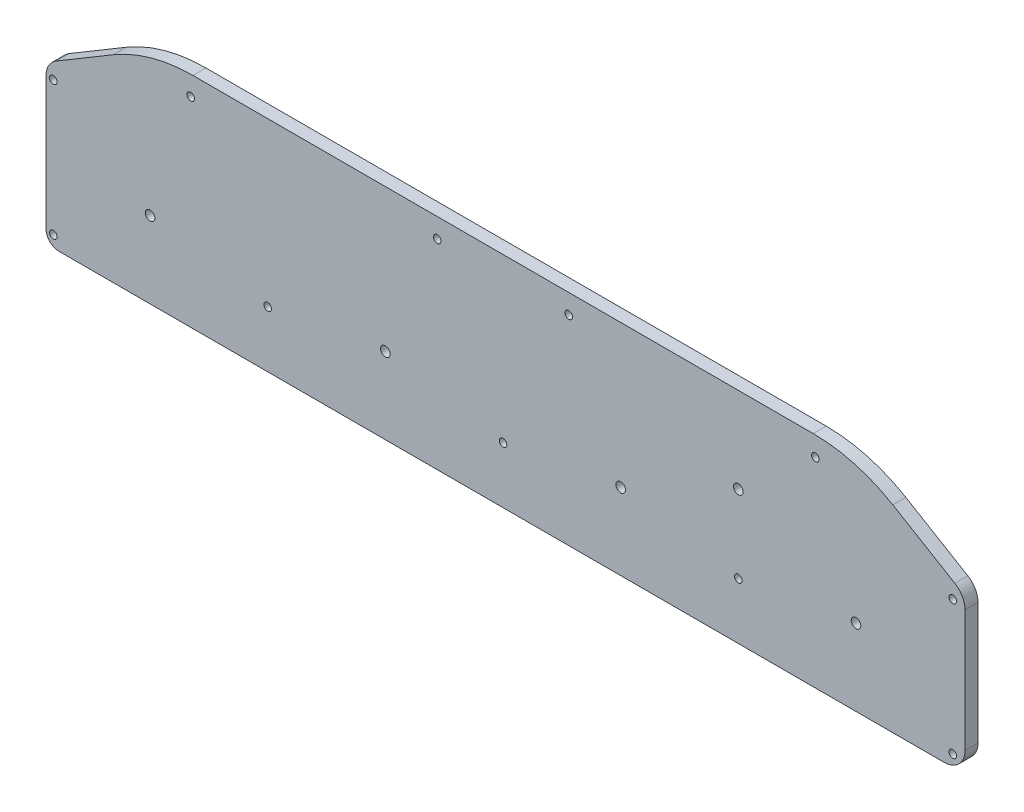
SolidWorks part; units mm, degrees
ref_plane "Front Plane" through (0, 0, 0) normal (0, 0, 1) x (1, 0, 0)
ref_plane "Top Plane" through (0, 0, 0) normal (0, 1, 0) x (1, 0, 0)
ref_plane "Right Plane" through (0, 0, 0) normal (1, 0, 0) x (0, 0, -1)
sketch "Sketch1" plane through (0, 0, 0) normal (0, 0, 1) x (1, 0, 0)
  line L0 (-228.6, 0) -> (228.6, 0) construction
  line L1 (0, -1000) -> (0, 49000) construction
  line L2 (0, 0) -> (0, -6.35)
  line L3 (-149.6188, -37.4478) -> (-217.2874, -37.4478)
  line L4 (226.06, -27.2878) -> (226.06, 32.3239)
  line L5 (220.0588, -31.7528) -> (-220.0588, -31.7528) construction
  line L6 (-223.6374, 33.766) -> (-223.6374, -31.0978)
  line L7 (-149.6188, -37.4478) -> (215.9, -37.4478)
  line L8 (-151.7577, 69.85) -> (151.7577, 69.85)
  line L9 (-240.1744, 69.85) -> (-240.1744, -37.4478) construction
  line L10 (-190.7328, 59.1281) -> (-218.6741, 42.4964)
  line L16 (190.7328, 59.1281) -> (221.0967, 41.0544)
  line L20 (-82.9742, 60.325) -> (-152.8242, 60.325) construction
  line L21 (-32.1742, 60.325) -> (-82.9742, 60.325) construction
  line L22 (32.1742, 60.325) -> (82.9742, 60.325) construction
  line L23 (82.9742, 60.325) -> (152.8242, 60.325) construction
  circle A0 centre (-172.72, 0) radius 50.8 construction
  circle A1 centre (172.72, 0) radius 50.8 construction
  circle A2 centre (-57.5742, 0) radius 50.8 construction
  circle A3 centre (57.5725, 0) radius 50.8 construction
  circle A4 centre (-172.72, 0) radius 2.35
  circle A5 centre (-57.5742, 0) radius 2.35
  circle A6 centre (57.5725, 0) radius 2.35
  circle A7 centre (172.72, 0) radius 2.35
  circle A8 centre (-172.72, 0) radius 32 construction
  circle A9 centre (-57.5742, 0) radius 32 construction
  circle A10 centre (57.5725, 0) radius 32 construction
  circle A11 centre (172.72, 0) radius 32 construction
  circle A12 centre (-115.1471, 27.9528) radius 32 construction
  circle A13 centre (-0.0009, 27.952) radius 32 construction
  circle A14 centre (115.1462, 27.9511) radius 32 construction
  circle A15 centre (-172.72, 0) radius 44 construction
  circle A16 centre (220.0588, -31.7528) radius 1.85
  circle A17 centre (115.1462, 27.9511) radius 2.35
  circle A18 centre (-220.0588, -31.7528) radius 1.85
  arc A19 (-217.2874, -37.4478) -> (-223.6374, -31.0978) centre (-217.2874, -31.0978) cw
  arc A20 (-223.6374, 33.766) -> (-218.6741, 42.4964) centre (-213.4774, 33.766) cw
  arc A21 (215.9, -37.4478) -> (226.06, -27.2878) centre (215.9, -27.2878) ccw
  arc A23 (221.0967, 41.0544) -> (226.06, 32.3239) centre (215.9, 32.3239) cw
  arc A24 (151.7577, 69.85) -> (190.7328, 59.1281) centre (151.7577, -6.35) cw
  arc A25 (-151.7577, 69.85) -> (-190.7328, 59.1281) centre (-151.7577, -6.35) ccw
  circle A37 centre (-32.1742, 60.325) radius 1.85
  circle A38 centre (-152.8242, 60.325) radius 1.85
  circle A39 centre (152.8242, 60.325) radius 1.85
  circle A40 centre (32.1742, 60.325) radius 1.85
  circle A42 centre (115.1454, -9.8972) radius 1.85
  circle A43 centre (-115.1471, -9.8972) radius 1.85
  circle A46 centre (-0.0013, -9.8972) radius 1.85
  circle A48 centre (220.0588, 33.8135) radius 1.85
  circle A49 centre (-220.0588, 33.8135) radius 1.85
  point P4 (0, 0)
  point P38 (0, -6.35)
  point P52 (-226.06, 38.1)
  point P57 (-172.72, 69.85)
  point P60 (226.06, 38.1)
  point P63 (172.72, 69.85)
  point P88 (-57.5742, 60.325)
  point P96 (57.5742, 60.325)
  dimension "D1" = 101.6
  dimension "D3" = 101.6
  dimension "D5" = 101.6
  dimension "D7" = 101.6
  dimension "D10" = 4.7
  dimension "D11" = 4.7
  dimension "D12" = 4.7
  dimension "D13" = 4.7
  dimension "D14" = 64
  dimension "D15" = 64
  dimension "D16" = 64
  dimension "D17" = 64
  dimension "D20" = 64
  dimension "D21" = 64
  dimension "D24" = 64
  dimension "D26" = 64
  dimension "D27" = 4.7
  dimension "D28" = 6.35
  dimension "D29" = 10.16
  dimension "D30" = 10.16
  dimension "D31" = 10.16
  dimension "D32" = 69.85
  dimension "D33" = 76.2
  dimension "D34" = 76.2
  dimension "D35" = 107.2978
  dimension "D2" = 55.88
  dimension "D4" = 55.88
  dimension "D6" = 115.1458
  dimension "D8" = 115.1467
  dimension "D9" = 115.1475
  dimension "D18" = 64
  dimension "D19" = 64
  dimension "D22" = 64
  dimension "D23" = 64
  dimension "D25" = 64
extrude "Boss-Extrude1" add sketch "Sketch1" along normal blind 6.35
